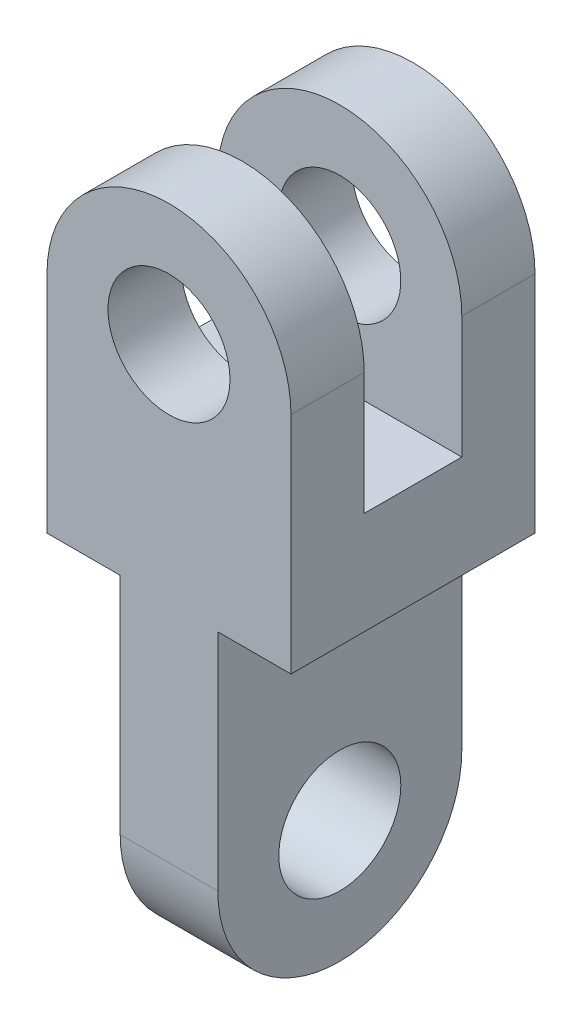
SolidWorks part; units mm, degrees
material "AISI 1020"
ref_plane "Alzado" through (0, 0, 0) normal (0, 0, 1) x (1, 0, 0)
ref_plane "Planta" through (0, 0, 0) normal (0, 1, 0) x (1, 0, 0)
ref_plane "Vista lateral" through (0, 0, 0) normal (1, 0, 0) x (0, 0, -1)
sketch "Croquis1" plane through (0, 0, 0) normal (0, 0, 1) x (1, 0, 0)
  line L0 (-50, 0) -> (-50, -92)
  line L1 (-50, -92) -> (50, -92)
  line L2 (50, -92) -> (50, 0)
  line L3 (-50, -50) -> (50, -50)
  circle A0 centre (0, 0) radius 25
  arc A1 (50, 0) -> (-50, 0) centre (0, 0) ccw
  dimension "D1" = 50
  dimension "D2" = 100
  dimension "D3" = 92
extrude "Saliente-Extruir1" add sketch "Croquis1" against normal blind 30 contours L2 A1 L0 L3 A0 | L3 L0 L1 L2
sketch "Croquis4" plane through (0, 0, -30) normal (0, 0, -1) x (-1, 0, 0)
  line L0 (-50, -50) -> (50, -50)
  line L1 (-50, -92) -> (-50, 0) construction
  line L2 (50, 0) -> (50, -92) construction
  line L3 (-50, -50) -> (-50, -92)
  line L4 (-50, -92) -> (50, -92)
  line L5 (50, -92) -> (50, -50)
  arc A0 (50, 0) -> (-50, 0) centre (0, 0) ccw construction
  point P9 (0, 50)
  dimension "D1" = 100
extrude "Saliente-Extruir2" add sketch "Croquis4" along normal blind 40
sketch "Croquis5" plane through (0, 0, -70) normal (0, 0, -1) x (-1, 0, 0)
  line L0 (-50, 0) -> (-50, -92)
  line L1 (-50, -92) -> (50, -92)
  line L2 (50, -92) -> (50, 0)
  circle A0 centre (0, 0) radius 25
  circle A1 centre (0, 0) radius 25 construction
  arc A2 (50, 0) -> (-50, 0) centre (0, 0) ccw
  arc A3 (50, 0) -> (-50, 0) centre (0, 0) ccw construction
extrude "Saliente-Extruir3" add sketch "Croquis5" along normal blind 30
sketch "Croquis6" plane through (0, 0, 0) normal (1, 0, 0) x (0, 0, -1)
  line L0 (0, -184) -> (0, -92)
  line L1 (0, -92) -> (100, -92)
  line L2 (100, -184) -> (100, -92)
  circle A0 centre (50, -184) radius 25
  arc A1 (0, -184) -> (100, -184) centre (50, -184) ccw
  point P3 (50, -234)
  dimension "D1" = 50
  dimension "D2" = 100
  dimension "D3" = 142
extrude "Saliente-Extruir4" add sketch "Croquis6" along normal blind 20 and the other way blind 20
